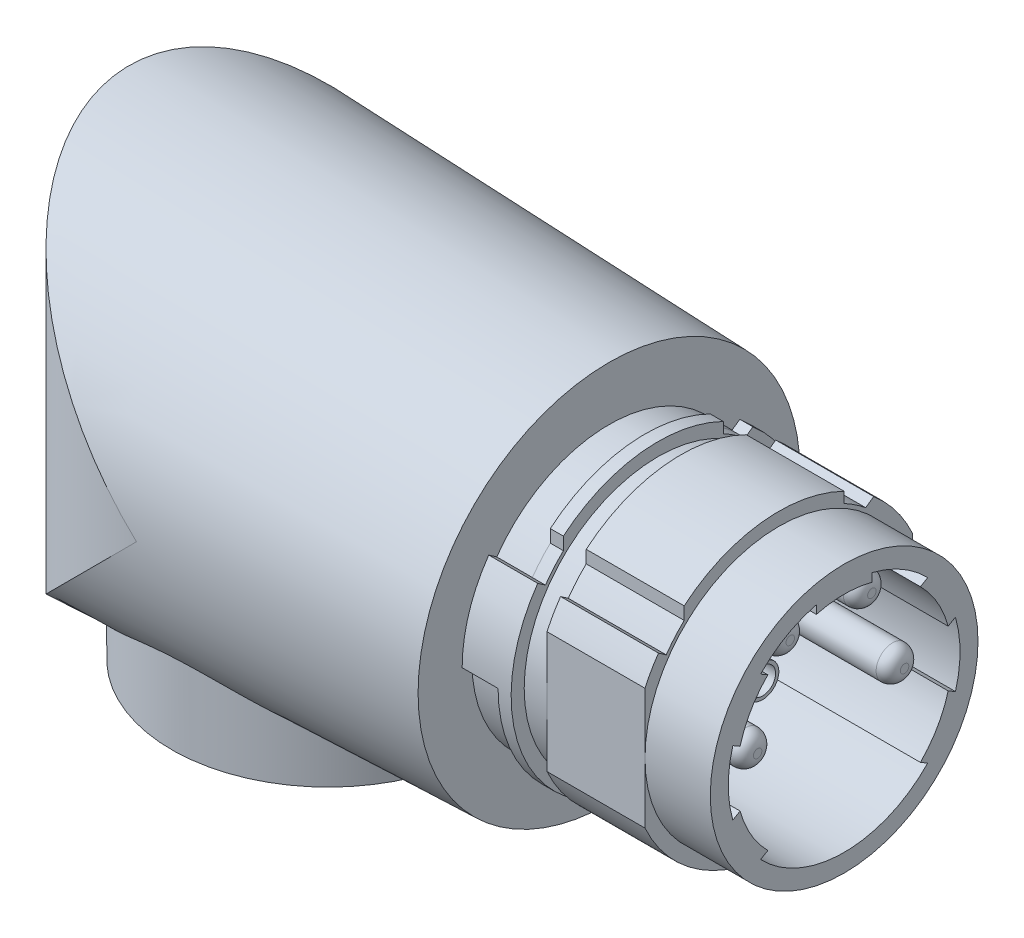
SolidWorks part; units mm, degrees
material "ABS"
ref_plane "Front Plane" through (0, 0, 0) normal (0, 0, 1) x (1, 0, 0)
ref_plane "Top Plane" through (0, 0, 0) normal (0, 1, 0) x (1, 0, 0)
ref_plane "Right Plane" through (0, 0, 0) normal (1, 0, 0) x (0, 0, -1)
sketch "Sketch3" plane through (0, 0, 0) normal (0, 0, 1) x (1, 0, 0)
  line L0 (-15.494, 16.0655) -> (40.132, 16.0655) construction
  line L4 (-15.494, 16.0655) -> (-15.494, 32.258)
  line L5 (-15.494, 32.258) -> (21.844, 30.9245)
  line L6 (21.844, 30.9245) -> (21.844, 28.7655)
  line L7 (21.844, 28.7655) -> (40.132, 28.7655)
  line L8 (40.132, 28.7655) -> (40.132, 16.0655)
  line L9 (40.132, 16.0655) -> (-15.494, 16.0655)
  line L11 (0, -17.187) -> (0, 17.187) construction
  line L12 (17.187, 0) -> (-17.187, 0) construction
  dimension "D1" = 15.494
  dimension "D2" = 32.385
  dimension "D3" = 29.718
  dimension "D4" = 25.4
  dimension "D5" = 16.0655
  dimension "D6" = 18.288
  dimension "D7" = 55.626
revolve "Revolve1" add sketch "Sketch3" angle 360 about L0
sketch "Sketch4" plane through (0, 0, 0) normal (0, 1, 0) x (1, 0, 0)
  line L0 (21.844, 14.859) -> (-15.494, 16.1925) construction
  line L2 (-15.494, 16.1925) -> (-15.494, -16.1925) construction
  line L3 (-15.494, -16.1925) -> (21.844, -14.859) construction
  line L5 (0.6882, 15.6146) -> (0.6882, 19.05)
  line L6 (0.6882, 19.05) -> (-24.7118, 19.05)
  line L7 (-24.7118, 19.05) -> (-24.7118, -19.05)
  line L8 (-24.7118, -19.05) -> (0.6882, -19.05)
  line L9 (0.6882, -19.05) -> (0.6882, -15.6146)
  line L10 (21.844, 14.859) -> (-15.494, 16.1925) construction
  line L12 (-15.494, -16.1925) -> (21.844, -14.859) construction
  line L14 (0.1305, 0) -> (-15.494, 0) construction
  arc A0 (0.6882, 15.6146) -> (0.6882, -15.6146) centre (0.1305, 0) ccw
  dimension "D1" = 38.1
  dimension "D2" = 25.4
extrude "Extrude3" cut sketch "Sketch4" along normal mid plane 91.44
sketch "Sketch5" plane through (0, 0, 0) normal (0, 0, 1) x (1, 0, 0)
  line L0 (21.844, 26.7335) -> (24.638, 26.7335)
  line L1 (21.844, 1.2065) -> (21.844, 30.9245) construction
  line L2 (24.638, 26.7335) -> (24.638, 27.4955)
  line L3 (24.638, 27.4955) -> (25.654, 27.4955)
  line L4 (27.432, 26.4795) -> (27.432, 27.4955)
  line L5 (27.432, 27.4955) -> (35.052, 27.4955)
  line L6 (35.052, 27.4955) -> (35.052, 26.4795)
  line L7 (35.052, 26.4795) -> (40.132, 26.4795)
  line L8 (40.132, 3.3655) -> (40.132, 28.7655) construction
  line L9 (40.132, 26.4795) -> (40.132, 28.7655)
  line L10 (40.132, 28.7655) -> (21.844, 28.7655)
  line L11 (21.844, 28.7655) -> (21.844, 26.7335)
  line L12 (0.6882, 16.0655) -> (40.132, 16.0655) construction
  line L13 (40.132, 16.0655) -> (21.844, 16.0655) construction
  line L14 (0.6882, 16.0655) -> (21.844, 16.0655) construction
  line L15 (25.654, 27.4955) -> (25.654, 26.4795)
  line L16 (25.654, 26.4795) -> (27.432, 26.4795)
  dimension "D1" = 20.828
  dimension "D2" = 22.86
  dimension "D3" = 20.828
  dimension "D4" = 22.86
  dimension "D5" = 21.336
  dimension "D6" = 5.08
  dimension "D7" = 12.7
  dimension "D8" = 1.778
  dimension "D9" = 15.494
revolve "Cut-Revolve1" cut sketch "Sketch5" angle 360 about L12
sketch "Sketch15" plane through (0, 0, 0) normal (0, 1, 0) x (1, 0, 0)
  circle A0 centre (0, 0) radius 12.192
  dimension "D1" = 24.384
extrude "Extrude12" add sketch "Sketch15" along normal blind 6.35
sketch "Sketch6" plane through (40.132, 0, 0) normal (1, 0, 0) x (0, 0, -1)
  line L0 (-7.366, 24.8055) -> (-7.366, 23.8226)
  line L1 (-8.7626, 22.2012) -> (-9.3629, 22.6215)
  line L2 (0, 19.7284) -> (0, -19.7284) construction
  line L3 (6.7564, 24.359) -> (7.3787, 24.7947)
  line L4 (5.08, 26.3046) -> (5.08, 25.4795)
  line L5 (0.254, 5.3713) -> (0.254, 4.6383)
  line L6 (3.8593, 6.0887) -> (4.572, 5.5897)
  circle A0 centre (0, 16.0655) radius 11.43 construction
  arc A1 (4.572, 5.5897) -> (0.254, 4.6383) centre (0, 16.0655) cw
  arc A2 (-7.366, 23.8226) -> (-8.7626, 22.2012) centre (0, 16.0655) ccw
  arc A3 (6.7564, 24.359) -> (5.08, 25.4795) centre (0, 16.0655) ccw
  arc A4 (7.3787, 24.7947) -> (5.08, 26.3046) centre (0, 16.0655) ccw
  arc A5 (-7.366, 24.8055) -> (-9.3629, 22.6215) centre (0, 16.0655) ccw
  arc A6 (3.8593, 6.0887) -> (0.254, 5.3713) centre (0, 16.0655) cw
  dimension "D1" = 10.6972
  dimension "D6" = 55
  dimension "D2" = 55
  dimension "D3" = 7.366
  dimension "D4" = 5.08
  dimension "D5" = 1.6764
  dimension "D7" = 0.254
  dimension "D8" = 4.572
  dimension "D9" = 55
extrude "Extrude4" cut sketch "Sketch6" against normal up to surface (18.288 mm away)
sketch "Sketch7" plane through (40.132, 0, 0) normal (1, 0, 0) x (0, 0, -1)
  circle A0 centre (0, 16.0655) radius 9.017
  dimension "D1" = 18.034
extrude "Extrude5" cut sketch "Sketch7" against normal blind 13.97
sketch "Sketch8" plane through (21.844, 0, 0) normal (1, 0, 0) x (0, 0, -1)
  line L0 (-9.3629, 22.6215) -> (-8.7626, 22.2012) construction
  line L1 (-9.3629, 22.6215) -> (-8.7626, 22.2012)
  line L2 (4.572, 5.5897) -> (3.8593, 6.0887) construction
  line L3 (4.572, 5.5897) -> (3.8305, 6.1089)
  line L4 (-8.7626, 22.2012) -> (-8.7387, 22.1844)
  line L5 (-10.668, 16.0655) -> (-11.43, 16.0655)
  line L6 (8.7387, 9.9466) -> (9.3629, 9.5095)
  arc A0 (4.572, 5.5897) -> (7.3787, 24.7947) centre (0, 16.0655) ccw construction
  arc A1 (4.572, 5.5897) -> (9.3629, 9.5095) centre (0, 16.0655) ccw
  circle A2 centre (0, 16.0655) radius 10.668 construction
  arc A3 (-8.7387, 22.1844) -> (-10.668, 16.0655) centre (0, 16.0655) ccw
  arc A4 (-9.3629, 22.6215) -> (0.254, 4.6383) centre (0, 16.0655) ccw construction
  arc A5 (-9.3629, 22.6215) -> (-11.43, 16.0655) centre (0, 16.0655) ccw
  arc A6 (3.8305, 6.1089) -> (8.7387, 9.9466) centre (0, 16.0655) ccw
extrude "Extrude6" add sketch "Sketch8" along normal up to surface (2.794 mm away) up to face at (24.638, 17.8433, 0.0017)
sketch "Sketch9" plane through (40.132, 0, 0) normal (1, 0, 0) x (0, 0, -1)
  line L0 (-9.017, 16.0655) -> (9.017, 16.0655) construction
  line L1 (-15.494, 22.4155) -> (-10.414, 22.4155)
  line L2 (-15.494, 22.4155) -> (-15.494, 9.7155)
  line L3 (-15.494, 9.7155) -> (-10.414, 9.7155)
  line L4 (-10.414, 22.4155) -> (-10.414, 9.7155)
  line L5 (15.494, 22.4155) -> (10.414, 22.4155)
  line L6 (15.494, 22.4155) -> (15.494, 9.7155)
  line L7 (15.494, 9.7155) -> (10.414, 9.7155)
  line L8 (10.414, 22.4155) -> (10.414, 9.7155)
  circle A0 centre (0, 16.0655) radius 10.414 construction
  circle A1 centre (0, 16.0655) radius 9.017 construction
  circle A2 centre (0, 16.0655) radius 9.017 construction
  dimension "D1" = 12.7
  dimension "D2" = 5.08
extrude "Extrude7" cut sketch "Sketch9" against normal up to surface (12.7 mm away) up to face at (27.432, 17.8433, 0.0017)
sketch "Sketch10" plane through (40.132, 0, 0) normal (1, 0, 0) x (0, 0, -1)
  line L0 (-2.159, 24.8202) -> (-2.159, 24.1647)
  line L1 (2.159, 24.1647) -> (2.159, 24.8202)
  line L2 (0, 32.258) -> (0, 16.0655) construction
  line L3 (0, 19.7284) -> (0, -19.7284) construction
  circle A0 centre (0, 16.0655) radius 9.017 construction
  arc A1 (2.159, 24.8202) -> (-2.159, 24.8202) centre (0, 16.0655) ccw
  arc A2 (2.159, 24.1647) -> (-2.159, 24.1647) centre (0, 16.0655) ccw
  spline S0 degree 3 poles (-15.6146, 16.0655) (-15.6186, 16.1773) (-15.6214, 16.2919) (-15.6246, 16.5181) (-15.6256, 16.8571) (-15.6157, 17.1949) (-15.5813, 17.8692) (-15.5391, 18.3167) (-15.3547, 19.6532) (-15.1551, 20.5364) (-14.7333, 21.8486) (-14.5721, 22.2839) (-14.2058, 23.15) (-14.0001, 23.5816) (-13.3217, 24.8493) (-12.7865, 25.6647) (-11.8407, 26.8366) (-11.5015, 27.2186) (-10.769, 27.9633) (-10.3761, 28.3251) (-9.132, 29.3552) (-8.2104, 29.977) (-6.6493, 30.7837) (-6.1065, 31.0271) (-4.9828, 31.4539) (-4.4004, 31.6381) (-3.4923, 31.8657) (-3.1824, 31.9335) (-2.5608, 32.0498) (-2.2486, 32.0985) (-1.3078, 32.216) (-0.6751, 32.2565) (0.6017, 32.2595) (1.2515, 32.2208) (2.5144, 32.0673) (3.1321, 31.9533) (4.3416, 31.6552) (4.9365, 31.4695) (6.0687, 31.0432) (6.61, 30.802) (7.6479, 30.2695) (8.1468, 29.9763) (9.0824, 29.3576) (9.5216, 29.0311) (10.35, 28.3481) (10.7391, 27.9916) (11.4715, 27.2511) (11.8162, 26.8652) (12.7723, 25.6857) (13.308, 24.8707) (14.2101, 23.1931) (14.5761, 22.3304) (15.1496, 20.5604) (15.352, 19.6686) (15.5385, 18.3235) (15.581, 17.8737) (15.6156, 17.1971) (15.6223, 16.9712) (15.6249, 16.6318) (15.6246, 16.5186) (15.6214, 16.2921) (15.6186, 16.1773) (15.6146, 16.0655) knots 0 0 0 0 0.007812 0.007812 0.015625 0.03125 0.03125 0.0625 0.0625 0.125 0.125 0.15625 0.15625 0.1875 0.1875 0.25 0.25 0.28125 0.28125 0.3125 0.3125 0.375 0.375 0.40625 0.40625 0.4375 0.4375 0.453125 0.453125 0.46875 0.46875 0.5 0.5 0.53125 0.53125 0.5625 0.5625 0.59375 0.59375 0.625 0.625 0.65625 0.65625 0.6875 0.6875 0.71875 0.71875 0.75 0.75 0.8125 0.8125 0.875 0.875 0.9375 0.9375 0.96875 0.96875 0.984375 0.984375 0.992187 0.992187 1 1 1 1 construction
  dimension "D1" = 16.764
  dimension "D2" = 4.318
extrude "Extrude8" add sketch "Sketch10" against normal up to surface (13.97 mm away) up to face at (26.162, 16.0655, -9.017)
pattern_circular "CirPattern1" count 6 over 360 about axis through (0, 16.0655, 0) along (1, 0, 0) skipping 3 of "Extrude8"
sketch "Sketch11" plane through (26.162, 0, 0) normal (1, 0, 0) x (0, 0, -1)
  line L0 (0, 24.4475) -> (0, 17.3926) construction
  line L1 (0, 19.7284) -> (0, -19.7284) construction
  circle A0 centre (-3.175, 22.4155) radius 1.27
  circle A1 centre (3.175, 22.4155) radius 1.27
  circle A2 centre (-5.715, 16.0655) radius 1.27
  circle A3 centre (5.715, 16.0655) radius 1.27
  arc A4 (2.159, 24.1647) -> (-2.159, 24.1647) centre (0, 16.0655) ccw construction
  dimension "D3" = 2.54
  dimension "D1" = 6.35
  dimension "D2" = 6.35
  dimension "D4" = 11.43
extrude "Extrude9" add sketch "Sketch11" along normal blind 12.954
sketch "Sketch12" plane through (26.162, 0, 0) normal (1, 0, 0) x (0, 0, -1)
  line L0 (0, 19.7284) -> (0, -19.7284) construction
  line L1 (0, 24.4475) -> (0, 5.6515) construction
  circle A0 centre (0, 16.0655) radius 1.27
  circle A1 centre (0, 16.0655) radius 1.016
  circle A2 centre (0, 12.8905) radius 1.27
  circle A3 centre (0, 12.8905) radius 1.016
  circle A4 centre (0, 9.4615) radius 1.016
  circle A5 centre (0, 9.4615) radius 1.27
  circle A6 centre (3.81, 11.6205) radius 1.27
  circle A7 centre (3.81, 11.6205) radius 1.016
  circle A8 centre (-3.81, 11.6205) radius 1.27
  circle A9 centre (-3.81, 11.6205) radius 1.016
  arc A10 (2.159, 24.1647) -> (-2.159, 24.1647) centre (0, 16.0655) ccw construction
  circle A11 centre (0, 16.0655) radius 10.414 construction
  dimension "D1" = 2.54
  dimension "D2" = 2.032
  dimension "D3" = 3.175
  dimension "D4" = 6.604
  dimension "D5" = 7.62
  dimension "D6" = 4.445
extrude "Extrude10" add sketch "Sketch12" along normal blind 3.81
fillet "Fillet1" radius 0.9398 4 edges at (39.116, 16.0655, 4.445) (39.116, 22.4155, 1.905) (39.116, 16.0655, -6.985) (39.116, 22.4155, -4.445)
